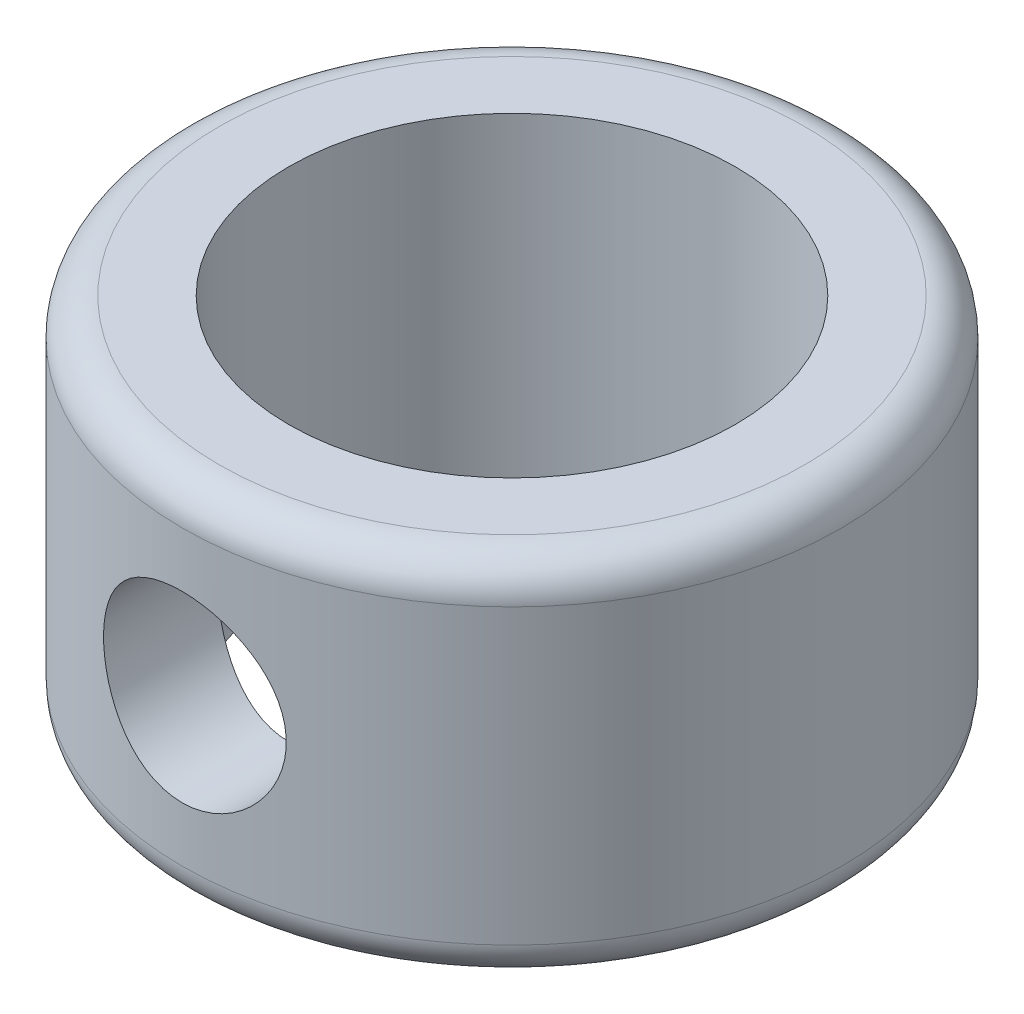
SolidWorks part; units mm, degrees
material "Brass"
ref_plane "Front Plane" through (0, 0, 0) normal (0, 0, 1) x (1, 0, 0)
ref_plane "Top Plane" through (0, 0, 0) normal (0, 1, 0) x (1, 0, 0)
ref_plane "Right Plane" through (0, 0, 0) normal (1, 0, 0) x (0, 0, -1)
sketch "Sketch1" plane through (0, 0, 0) normal (0, 1, 0) x (1, 0, 0)
  circle A0 centre (0, 0) radius 4.5
  dimension "D1" = 9
extrude "Boss-Extrude1" add sketch "Sketch1" along normal blind 5
hole_wizard "Ø6.1 (6.1) Diameter Hole1" positions "Sketch2" profile "Sketch3" hole size "Ø6.1" standard "ISO" end condition through all
sketch "Sketch2" plane through (0, 5, 0) normal (0, 1, 0) x (1, 0, 0)
  point P0 (0, 0)
sketch "Sketch3" plane through (0, 5, 0) normal (1, 0, 0) x (0, 0, 1)
  line L0 (0, 0) -> (0, 5)
  line L1 (0, 5) -> (3.05, 5)
  line L2 (3.05, 5) -> (3.05, 0)
  line L5 (3.05, 0) -> (0, 0)
  line L11 (0, -6.35) -> (0, 107.95) construction
  dimension "Thru Hole Dia." = 6.1
  dimension "Thru Hole Depth" = 5
hole_wizard "M3 Tapped Hole1" positions "Sketch5" profile "Sketch6" tap size "M3" standard "ISO"
sketch "Sketch5" plane through (0, 0, 0) normal (0, 0, 1) x (1, 0, 0)
  line L0 (4.95, 0) -> (-4.95, 0) construction
  point P0 (-0.0071, 2.5)
  point P22 (-0.0071, 2.5)
  point P24 (-0.0071, 2.5)
  point P26 (-0.0071, 2.5)
  dimension "D1" = 2.5
sketch "Sketch6" plane through (-0.0071, 2.5, 0) normal (1, 0, 0) x (0, 1, 0)
  line L0 (0, 0) -> (0, 4.5)
  line L1 (0, 4.5) -> (1.25, 4.5)
  line L2 (1.25, 4.5) -> (1.25, 0)
  line L5 (1.25, 0) -> (0, 0)
  line L11 (0, -6.35) -> (0, 107.95) construction
  dimension "Thru Tap Drill Dia." = 2.5
  dimension "Thru Tap Drill Depth" = 4.5
cosmetic thread "Hole Thread1"
fillet "Fillet1" radius 0.5 2 edges at (0, 0, 4.5) (0, 5, 4.5)
